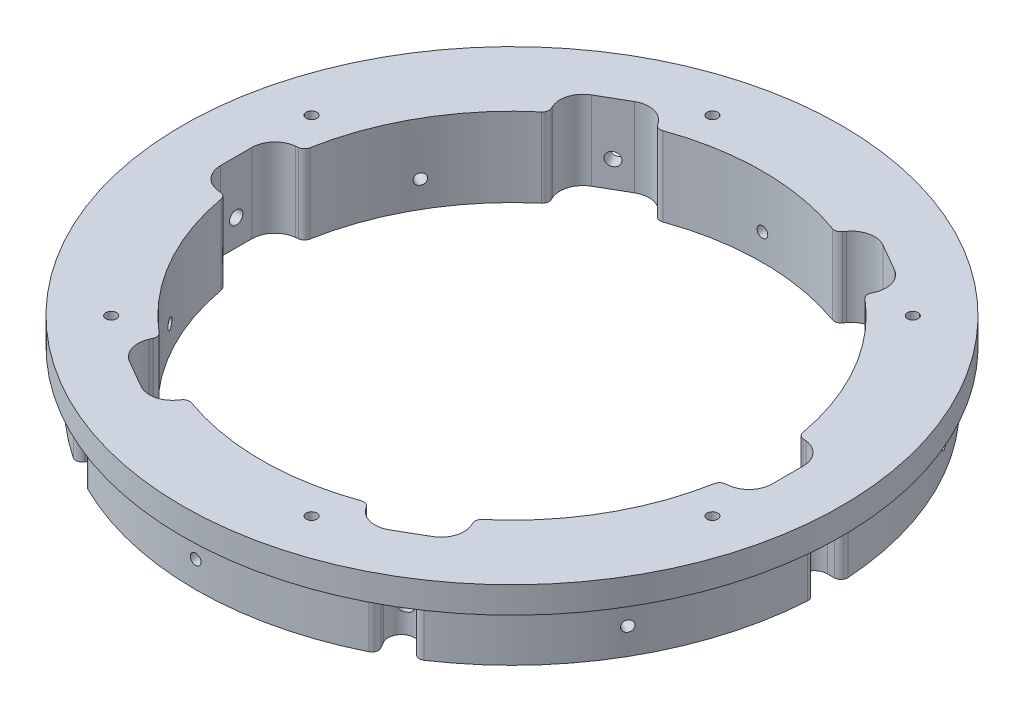
SolidWorks part; units mm, degrees
material "6061-T6 (SS)"
ref_plane "Front Plane" through (0, 0, 0) normal (0, 0, 1) x (1, 0, 0)
ref_plane "Top Plane" through (0, 0, 0) normal (0, 1, 0) x (1, 0, 0)
ref_plane "Right Plane" through (0, 0, 0) normal (1, 0, 0) x (0, 0, -1)
sketch "Sketch1" plane through (0, 0, 0) normal (0, 1, 0) x (1, 0, 0)
  circle A0 centre (0, 0) radius 76.2
  circle A1 centre (0, 0) radius 60.325
  dimension "D1" = 152.4
  dimension "D2" = 120.65
extrude "Boss-Extrude1" add sketch "Sketch1" against normal blind 19.05
sketch "Sketch3" plane through (0, -19.05, 0) normal (0, -1, 0) x (-1, 0, 0)
  line L0 (-76.1338, 3.175) -> (-72.771, 3.175)
  line L1 (-76.1338, -3.175) -> (-72.771, -3.175)
  circle A0 centre (0, 0) radius 76.2 construction
  arc A1 (-72.771, 3.175) -> (-72.771, -3.175) centre (-72.771, 0) cw
  arc A2 (-76.1338, -3.175) -> (-76.1338, 3.175) centre (0, 0) cw
  point P9 (-69.596, 0)
  point P13 (-76.2, 0)
  dimension "D1" = 6.35
  dimension "D2" = 6.604
extrude "Cut-Extrude1" cut sketch "Sketch3" against normal blind 12.7
sketch "Sketch4" plane through (0, -19.05, 0) normal (0, -1, 0) x (-1, 0, 0)
  line L0 (-66.421, 8.7312) -> (-66.421, -8.7312)
  line L1 (-66.421, -8.7312) -> (-59.5683, -9.525)
  line L2 (-59.5683, -9.525) -> (-59.5683, 9.525)
  line L3 (-59.5683, 9.525) -> (-66.421, 8.7312)
  line L4 (-66.421, 0) -> (0, 0) construction
  circle A0 centre (0, 0) radius 60.325 construction
  dimension "D1" = 3.175
  dimension "D2" = 19.05
  dimension "D3" = 17.4625
extrude "Cut-Extrude2" cut sketch "Sketch4" against normal through all
hole_wizard "1/8 (0.125) Diameter Hole1" positions "Sketch5" profile "Sketch6" hole size "1/8" standard "ANSI Inch"
sketch "Sketch5" plane through (66.421, 0, 0) normal (-1, 0, 0) x (0, 0, 1)
  line L0 (-8.7312, -19.05) -> (8.7312, -19.05) construction
  point P0 (0, -12.7)
  dimension "D1" = 6.35
sketch "Sketch6" plane through (66.421, -12.7, 0) normal (0, 1, 0) x (0, 0, 1)
  line L0 (0, 0) -> (0, 9.779)
  line L1 (0, 9.779) -> (1.5875, 9.779)
  line L2 (1.5875, 9.779) -> (1.5875, 0)
  line L5 (1.5875, 0) -> (0, 0)
  line L11 (0, -6.35) -> (0, 107.95) construction
  dimension "Thru Hole Dia." = 3.175
  dimension "Thru Hole Depth" = 9.779
fillet "Fillet1" radius 1.5875 4 edges at (76.1338, -12.7, 3.175) (76.1338, -12.7, -3.175) (59.5683, -9.525, 9.525) (59.5683, -9.525, -9.525)
fillet "Fillet2" radius 5.5562 2 edges at (66.421, -9.525, 8.7312) (66.421, -9.525, -8.7312)
sketch "Sketch9" plane through (0, 0, 0) normal (0, 0, 1) x (1, 0, 0)
  line L0 (-76.2, -19.05) -> (76.0446, -19.05) construction
  circle A0 centre (0, -12.7) radius 1.2891
  dimension "D1" = 2.5781
  dimension "D2" = 6.35
extrude "Cut-Extrude3" cut sketch "Sketch9" against normal through all
sketch "Sketch11" plane through (0, -19.05, 0) normal (0, -1, 0) x (1, 0, 0)
  line L0 (0, 0) -> (76.2, 0) construction
  line L1 (0, 0) -> (65.9365, 17.6676) construction
  line L2 (58.2695, 15.6133) -> (73.6035, 19.722) construction
  circle A0 centre (65.9365, 17.6676) radius 1.289
  arc A1 (76.0446, -4.8638) -> (76.0446, 4.8638) centre (0, 0) ccw construction
  arc A2 (59.3714, 10.6838) -> (59.3714, -10.6838) centre (0, 0) ccw construction
  arc A3 (76.0446, 4.8638) -> (76.0446, -4.8638) centre (0, 0) ccw construction
  point P18 (65.9365, 17.6676)
  dimension "D1" = 2.5781
  dimension "D2" = 15
extrude "Cut-Extrude5" cut sketch "Sketch11" against normal through all
pattern_circular "CirPattern1" count 6 over 360 about axis through (0, 0, 0) along (0, 1, 0) of "Cut-Extrude1", "Cut-Extrude2", "Fillet2", "Fillet1", "1/8 (0.125) Diameter Hole1", "Cut-Extrude3", "Cut-Extrude5"
sketch "Sketch8" plane through (0, 0, 0) normal (0, 1, 0) x (1, 0, 0)
  circle A0 centre (0, 0) radius 79.375
  circle A1 centre (0, 0) radius 76.2
  circle A2 centre (0, 0) radius 76.2 construction
  dimension "D1" = 3.175
extrude "Boss-Extrude3" add sketch "Sketch8" against normal up to surface (6.35 mm away) up to face at (-74.0439, -6.35, 0)
